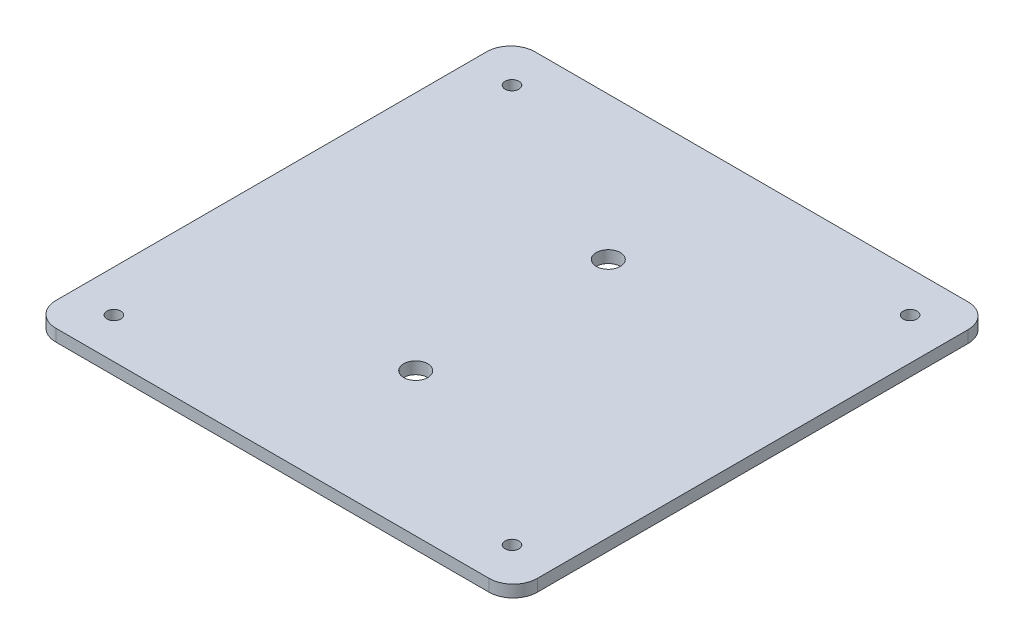
SolidWorks part; units mm, degrees
material "Acrylic (Medium-high impact)"
ref_plane "Front" through (0, 0, 0) normal (0, 0, 1) x (1, 0, 0)
ref_plane "Top" through (0, 0, 0) normal (0, 1, 0) x (1, 0, 0)
ref_plane "Right" through (0, 0, 0) normal (1, 0, 0) x (0, 0, -1)
sketch "Sketch1" plane through (0, 0, 0) normal (0, 1, 0) x (1, 0, 0)
  line L0 (0, 0) -> (0, 25.4) construction
  line L1 (-52.5145, 52.5145) -> (52.5145, 52.5145) construction
  line L2 (-52.5145, 52.5145) -> (-52.5145, -52.5145) construction
  line L3 (-52.5145, -52.5145) -> (52.5145, -52.5145) construction
  line L4 (52.5145, 52.5145) -> (52.5145, -52.5145) construction
  line L5 (-52.5145, 52.5145) -> (52.5145, -52.5145) construction
  line L6 (-52.5145, -52.5145) -> (52.5145, 52.5145) construction
  line L7 (-63.5, 63.1798) -> (63.5, 63.1798)
  line L8 (-63.5, 63.1798) -> (-63.5, -63.1798)
  line L9 (-63.5, -63.1798) -> (63.5, -63.1798)
  line L10 (63.5, 63.1798) -> (63.5, -63.1798)
  line L11 (-63.5, 63.1798) -> (63.5, -63.1798) construction
  line L12 (-63.5, -63.1798) -> (63.5, 63.1798) construction
  line L13 (-25.4, 25.4) -> (25.4, 25.4) construction
  line L14 (-25.4, 25.4) -> (-25.4, -25.4) construction
  line L15 (-25.4, -25.4) -> (25.4, -25.4) construction
  line L16 (25.4, 25.4) -> (25.4, -25.4) construction
  line L17 (-25.4, 25.4) -> (25.4, -25.4) construction
  line L18 (-25.4, -25.4) -> (25.4, 25.4) construction
  line L19 (0, 0) -> (0, -25.4) construction
  circle A0 centre (-52.5145, 52.5145) radius 1.8288
  circle A1 centre (52.5145, 52.5145) radius 1.8288
  circle A2 centre (52.5145, -52.5145) radius 1.8288
  circle A3 centre (-52.5145, -52.5145) radius 1.8288
  circle A4 centre (-25.4, 25.4) radius 3.175 construction
  circle A5 centre (25.4, 25.4) radius 3.175 construction
  circle A6 centre (25.4, -25.4) radius 3.175 construction
  circle A7 centre (-25.4, -25.4) radius 3.175 construction
  circle A8 centre (0, 0) radius 3.175 construction
  circle A9 centre (0, 25.4) radius 3.175
  circle A10 centre (0, -25.4) radius 3.175
  point P0 (0, 0)
  point P10 (0, 0)
  point P15 (0, 0)
  dimension "D3" = 3.6576
  dimension "D8" = 6.35
  dimension "D9" = 6.35
  dimension "D1" = 105.029
  dimension "D2" = 105.029
  dimension "D4" = 127
  dimension "D5" = 126.3596
  dimension "D6" = 50.8
  dimension "D7" = 50.8
  dimension "D10" = 50.8
extrude "Boss-Extrude1" add sketch "Sketch1" along normal blind 3.175
fillet "Fillet1" radius 6.35 4 edges at (-63.5, 1.5875, -63.1798) (63.5, 1.5875, -63.1798) (63.5, 1.5875, 63.1798) (-63.5, 1.5875, 63.1798)
